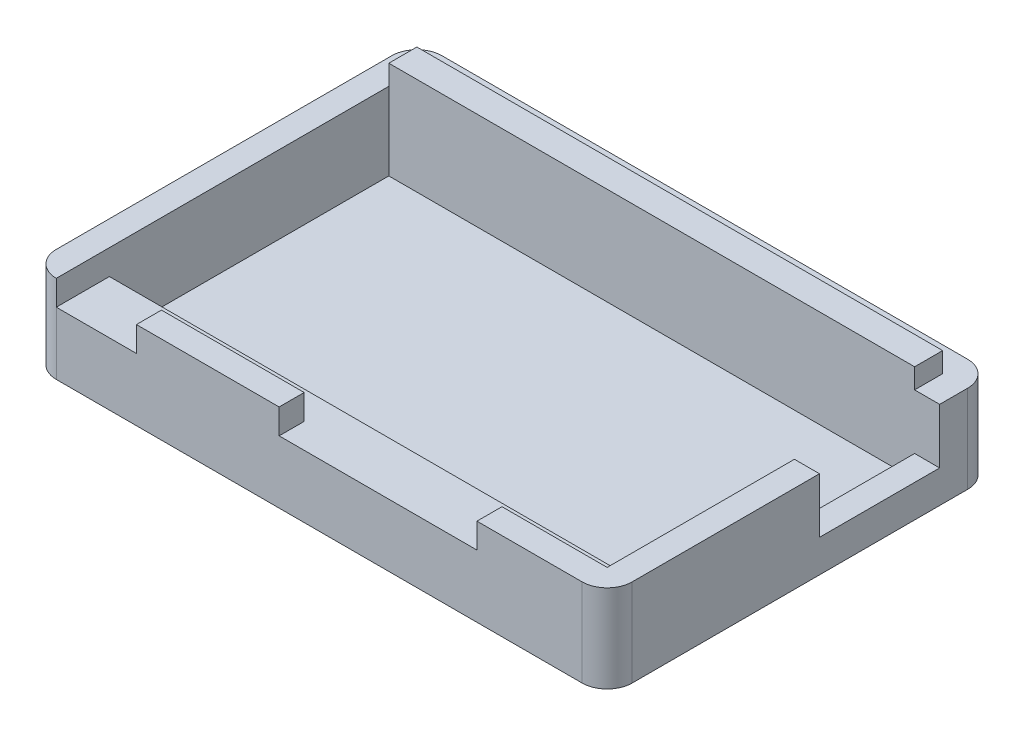
SolidWorks part; units mm, degrees
ref_plane "Front" through (0, 0, 0) normal (0, 0, 1) x (1, 0, 0)
ref_plane "Top" through (0, 0, 0) normal (0, 1, 0) x (1, 0, 0)
ref_plane "Right" through (0, 0, 0) normal (1, 0, 0) x (0, 0, -1)
sketch "Sketch1" plane through (0, 0, 0) normal (0, 1, 0) x (1, 0, 0)
  line L0 (0, 0) -> (0, 38.5)
  line L1 (0, 38.5) -> (57.5, 38.5)
  line L2 (57.5, 38.5) -> (57.5, 0)
  line L3 (57.5, 0) -> (0, 0)
  line L4 (2.5, 36) -> (2.5, 2.5)
  line L5 (2.5, 2.5) -> (55, 2.5)
  line L6 (55, 2.5) -> (55, 36)
  line L7 (55, 36) -> (2.5, 36)
  dimension "D1" = 33.5
  dimension "D2" = 52.5
  dimension "D3" = 57.5
  dimension "D4" = 2.5
  dimension "D5" = 38.5
  dimension "D6" = 2.5
extrude "Boss-Extrude1" add sketch "Sketch1" along normal blind 10.25
sketch "Sketch10" plane through (0, 0, 0) normal (0, 1, 0) x (1, 0, 0)
  line L1 (2.5, 36) -> (55, 36)
  line L2 (2.5, 36) -> (2.5, 2.5)
  line L3 (2.5, 2.5) -> (55, 2.5)
  line L4 (55, 36) -> (55, 2.5)
extrude "Boss-Extrude8" add sketch "Sketch10" along normal blind 2.5
sketch "Sketch11" plane through (0, 2.5, 0) normal (0, 1, 0) x (1, 0, 0)
  line L0 (55, 2.5) -> (55, 36) construction
  line L1 (2.5, 36) -> (55, 36)
  line L2 (2.5, 36) -> (2.5, 33.2)
  line L3 (2.5, 33.2) -> (55, 33.2)
  line L4 (55, 36) -> (55, 33.2)
  dimension "D1" = 2.8
extrude "Boss-Extrude9" add sketch "Sketch11" along normal blind 9.75
sketch "Sketch12" plane through (0, 2.5, 0) normal (0, 1, 0) x (1, 0, 0)
  line L0 (55, 2.5) -> (55, 33.2) construction
  line L1 (2.5, 2.5) -> (55, 2.5)
  line L2 (2.5, 2.5) -> (2.5, 5.3)
  line L3 (2.5, 5.3) -> (55, 5.3)
  line L4 (55, 2.5) -> (55, 5.3)
  dimension "D1" = 2.8
extrude "Boss-Extrude10" add sketch "Sketch12" along normal blind 5.25
sketch "Sketch13" plane through (57.5, 0, 0) normal (1, 0, 0) x (0, 0, -1)
  line L0 (23.2, 10.25) -> (23.2, 7.25) construction
  line L1 (33.2, 4.75) -> (21.2, 4.75)
  line L2 (33.2, 4.75) -> (33.2, 10.25)
  line L3 (33.2, 10.25) -> (21.2, 10.25)
  line L4 (21.2, 4.75) -> (21.2, 10.25)
  line L5 (23.2, 7.25) -> (31.2, 7.25) construction
  line L6 (0, 10.25) -> (38.5, 10.25) construction
  line L7 (38.5, 10.25) -> (36, 10.25) construction
  line L8 (31.2, 7.25) -> (31.2, 10.25) construction
  line L10 (27.2, 7.25) -> (27.2, 10.25) construction
  point P15 (0, 0)
  point P16 (0, 0)
  point P17 (29.7922, 10.25)
  point P18 (27.5379, 10.25)
  dimension "D1" = 2.5
  dimension "D2" = 12
  dimension "D3" = 5.5
  dimension "D4" = 2.8
  dimension "D5" = 8
  dimension "D6" = 3
  dimension "D7" = 4.8
extrude "Cut-Extrude1" cut sketch "Sketch13" against normal up to surface (2.5 mm away) up to face at (55, 6.8333, -13.6667)
sketch "Sketch14" plane through (0, 0, -2.5) normal (0, 0, -1) x (-1, 0, 0)
  line L0 (-2.5, 10.25) -> (-55, 10.25) construction
  line L1 (-2.5, 10.25) -> (-10.5, 10.25)
  line L2 (-2.5, 10.25) -> (-2.5, 7.75)
  line L3 (-2.5, 7.75) -> (-10.5, 7.75)
  line L4 (-10.5, 10.25) -> (-10.5, 7.75)
  line L15 (-44.5, 10.25) -> (-24.75, 10.25)
  line L16 (-44.5, 10.25) -> (-44.5, 7.75)
  line L17 (-44.5, 7.75) -> (-24.75, 7.75)
  line L18 (-24.75, 10.25) -> (-24.75, 7.75)
  dimension "D1" = 19.75
  dimension "D2" = 2.5
  dimension "D3" = 8
  dimension "D4" = 2.5
  dimension "D5" = 14.25
extrude "Cut-Extrude2" cut sketch "Sketch14" against normal up to surface (2.5 mm away) up to face at (28.75, 5.125, 0)
sketch "Sketch15" plane through (0, 0, 0) normal (-1, 0, 0) x (0, 0, 1)
  line L0 (0, 10.25) -> (0, 0) construction
  line L1 (-38.5, 0) -> (0, 0)
  line L2 (-38.5, 0) -> (-38.5, 1.5)
  line L3 (-38.5, 1.5) -> (0, 1.5)
  line L4 (0, 0) -> (0, 1.5)
  dimension "D1" = 1.5
extrude "Cut-Extrude3" cut sketch "Sketch15" against normal up to surface (57.5 mm away) up to face at (57.5, 6.3125, -23.225)
fillet "Fillet1" radius 2.5 4 edges at (0, 5.875, 0) (0, 5.875, -38.5) (57.5, 5.875, -38.5) (57.5, 5.875, 0)
